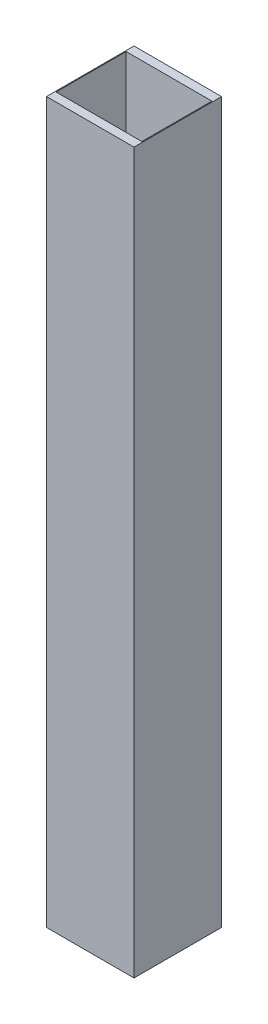
SolidWorks part; units mm, degrees
ref_plane "Front Plane" through (0, 0, 0) normal (0, 0, 1) x (1, 0, 0)
ref_plane "Top Plane" through (0, 0, 0) normal (0, 1, 0) x (1, 0, 0)
ref_plane "Right Plane" through (0, 0, 0) normal (1, 0, 0) x (0, 0, -1)
sketch "Sketch1" plane through (0, 0, 0) normal (0, 1, 0) x (1, 0, 0)
  line L1 (-2.5, -2.5) -> (2.5, -2.5)
  line L2 (-2.5, -2.5) -> (-2.5, 2.5)
  line L3 (-2.5, 2.5) -> (2.5, 2.5)
  line L4 (2.5, -2.5) -> (2.5, 2.5)
  line L5 (-2.5, -2.5) -> (2.5, 2.5) construction
  line L6 (-2.5, 2.5) -> (2.5, -2.5) construction
  line L11 (-2.45, 2) -> (2.45, 2)
  line L12 (-2.45, 2) -> (-2.45, -2)
  line L13 (-2.45, -2) -> (2.45, -2)
  line L14 (2.45, 2) -> (2.45, -2)
  line L15 (-2.45, 2) -> (2.45, -2) construction
  line L16 (-2.45, -2) -> (2.45, 2) construction
  point P0 (0, 0)
  point P6 (0, 0)
  point P7 (0, 0)
  dimension "D1" = 5
  dimension "D2" = 5
  dimension "D3" = 4
  dimension "D4" = 4.9
extrude "Boss-Extrude1" add sketch "Sketch1" along normal blind 41.1
sketch "Sketch2" plane through (-2.5, 0, 0) normal (-1, 0, 0) x (0, 0, 1)
  line L0 (-2.5, 41.1) -> (-2.5, 0) construction
  line L1 (-1.25, 1) -> (1.25, 1)
  line L2 (-1.25, 1) -> (-1.25, 3.5)
  line L3 (-1.25, 3.5) -> (1.25, 3.5)
  line L4 (1.25, 1) -> (1.25, 3.5)
  line L5 (-1.25, 1) -> (1.25, 3.5) construction
  line L6 (-1.25, 3.5) -> (1.25, 1) construction
  line L7 (-2.5, 0) -> (2.5, 0) construction
  point P0 (0, 2.25)
  dimension "D1" = 2.5
  dimension "D2" = 2.5
  dimension "D3" = 2.5
  dimension "D4" = 1
extrude "Cut-Extrude1" cut sketch "Sketch2" against normal up to surface (0.05 mm away) and the other way through all up to face at (-2.45, 20.55, 0)
